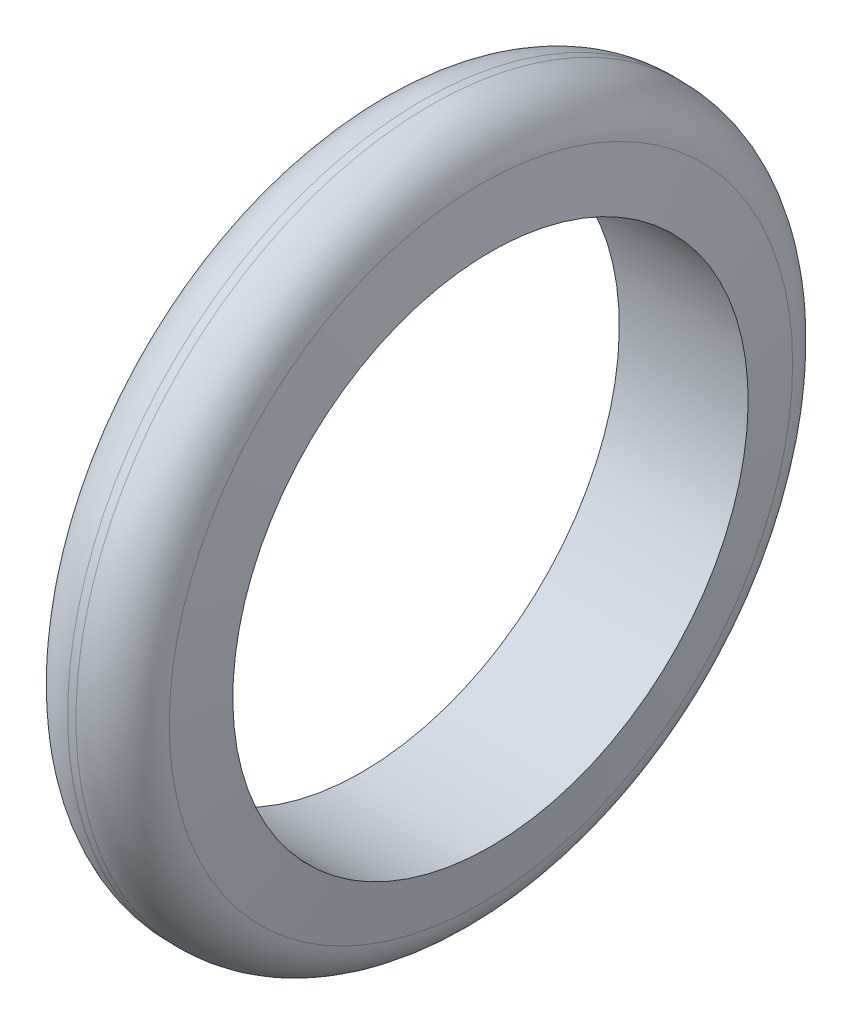
SolidWorks part; units mm, degrees
ref_plane "Front Plane" through (0, 0, 0) normal (0, 0, 1) x (1, 0, 0)
ref_plane "Top Plane" through (0, 0, 0) normal (0, 1, 0) x (1, 0, 0)
ref_plane "Right Plane" through (0, 0, 0) normal (1, 0, 0) x (0, 0, -1)
sketch "Sketch2" plane through (0, 0, 0) normal (0, 0, 1) x (1, 0, 0)
  line L0 (0, 0) -> (0, 103.5573) construction
  line L1 (0, 0) -> (108.5158, 0) construction
  line L2 (-7.3551, 55) -> (7.3551, 55)
  line L3 (-10, 40) -> (10, 40)
  line L4 (7.3551, 55) -> (10, 40)
  line L5 (-7.3551, 55) -> (-10, 40)
  dimension "D1" = 80
  dimension "D2" = 110
  dimension "D3" = 20
  dimension "D4" = 10
revolve "Revolve4" add sketch "Sketch2" angle 360 about L1
fillet "Fillet1" radius 8 2 edges at (-7.3551, -55, 0) (7.3551, -55, 0)
